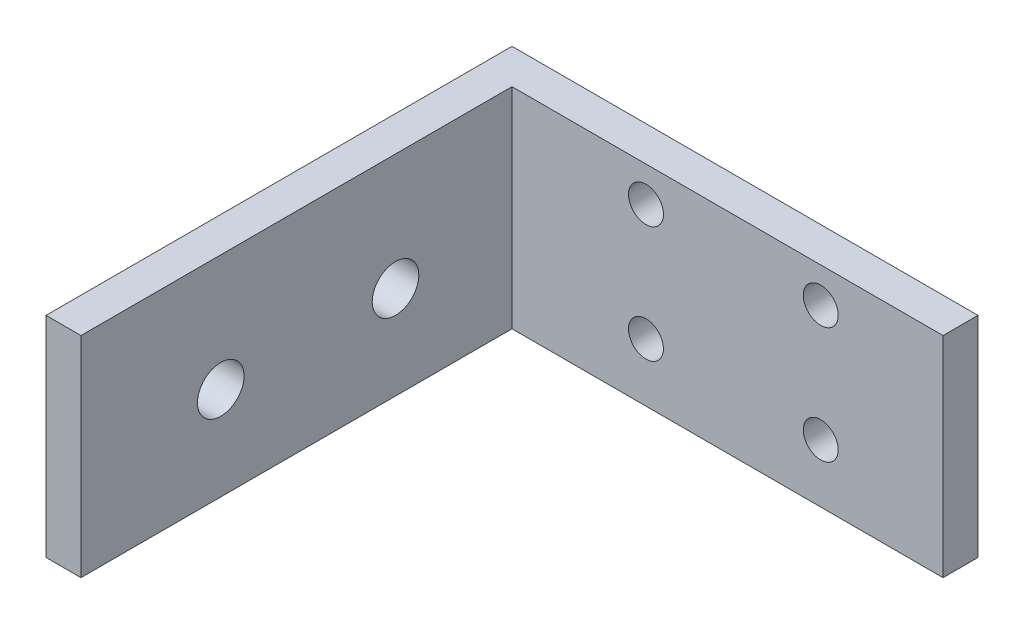
SolidWorks part; units mm, degrees
ref_plane "Plan de face" through (0, 0, 0) normal (0, 0, 1) x (1, 0, 0)
ref_plane "Plan de dessus" through (0, 0, 0) normal (0, 1, 0) x (1, 0, 0)
ref_plane "Plan de droite" through (0, 0, 0) normal (1, 0, 0) x (0, 0, -1)
sketch "Esquisse1" plane through (0, 0, 0) normal (0, 0, 1) x (1, 0, 0)
  line L1 (0, 0) -> (40, 0)
  line L2 (0, 0) -> (0, 18)
  line L3 (0, 18) -> (40, 18)
  line L4 (40, 0) -> (40, 18)
  dimension "D1" = 18
  dimension "D2" = 40
extrude "Boss.-Extru.1" add sketch "Esquisse1" along normal blind 3
sketch "Esquisse2" plane through (0, 0, 3) normal (0, 0, 1) x (1, 0, 0)
  line L0 (0, 0) -> (40, 0) construction
  line L1 (0, 18) -> (3, 18)
  line L2 (0, 18) -> (0, 0)
  line L3 (0, 0) -> (3, 0)
  line L4 (3, 18) -> (3, 0)
  dimension "D1" = 3
extrude "Boss.-Extru.2" add sketch "Esquisse2" along normal blind 37
sketch "Esquisse3" plane through (0, 0, 3) normal (0, 0, 1) x (1, 0, 0)
  line L0 (3, 0) -> (3, 18) construction
  line L4 (3, 0) -> (40, 0) construction
  circle A0 centre (14.5, 15) radius 1.5
  circle A1 centre (29.5, 15) radius 1.5
  circle A2 centre (14.5, 5) radius 1.5
  circle A3 centre (29.5, 5) radius 1.5
  dimension "D2" = 3
  dimension "D3" = 3
  dimension "D4" = 3
  dimension "D5" = 15
  dimension "D1" = 3
  dimension "D6" = 10
  dimension "D7" = 11.5
  dimension "D8" = 11.5
  dimension "D9" = 10
  dimension "D10" = 15
  dimension "D11" = 5
  dimension "D12" = 5
extrude "Enlèv. mat.-Extru.1" cut sketch "Esquisse3" against normal through all
sketch "Esquisse4" plane through (3, 0, 0) normal (1, 0, 0) x (0, 0, -1)
  line L0 (-40, 18) -> (-3, 18) construction
  line L1 (-3, 0) -> (-3, 18) construction
  circle A0 centre (-28, 8) radius 2
  circle A1 centre (-13, 8) radius 2
  dimension "D1" = 4
  dimension "D2" = 4
  dimension "D3" = 15
  dimension "D4" = 10
  dimension "D5" = 10
  dimension "D6" = 10
extrude "Enlèv. mat.-Extru.2" cut sketch "Esquisse4" against normal through all
